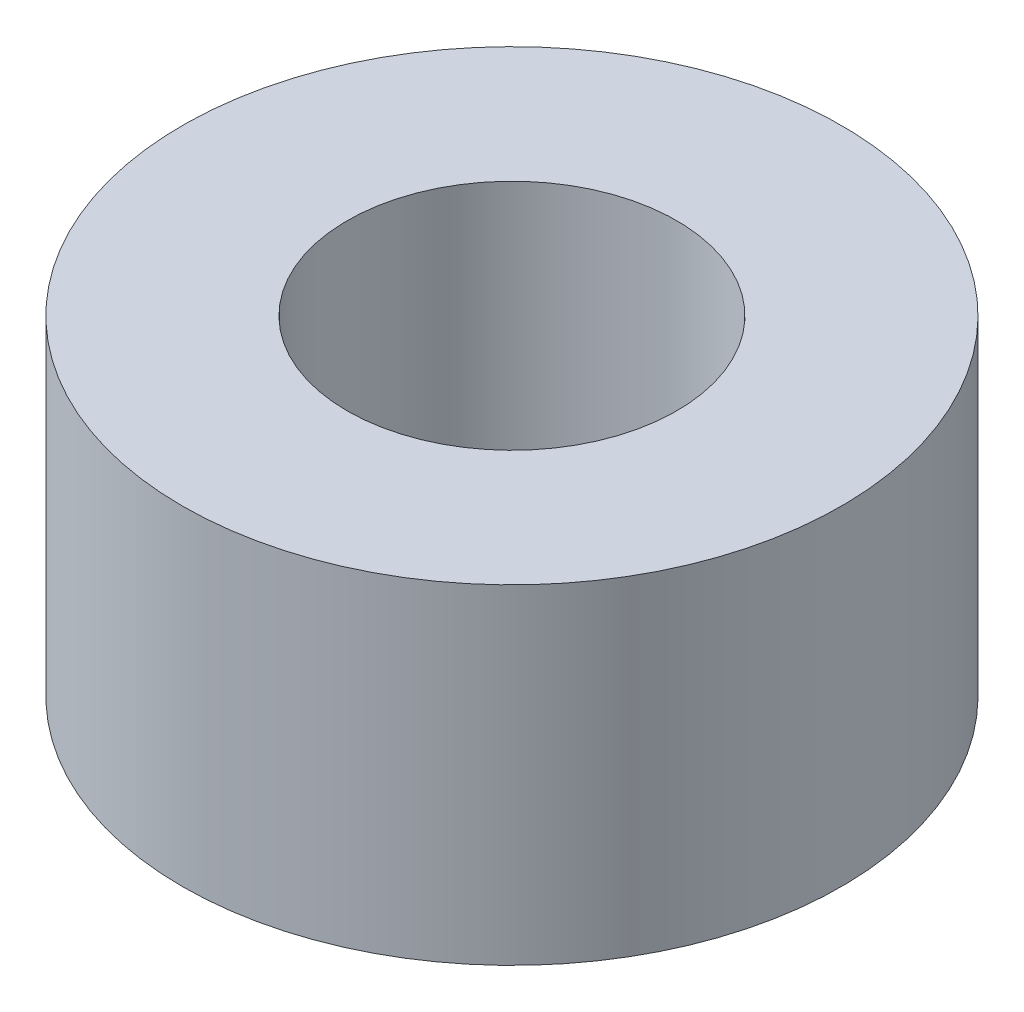
SolidWorks part; units mm, degrees
ref_plane "前视基准面" through (0, 0, 0) normal (0, 0, 1) x (1, 0, 0)
ref_plane "上视基准面" through (0, 0, 0) normal (0, 1, 0) x (1, 0, 0)
ref_plane "右视基准面" through (0, 0, 0) normal (1, 0, 0) x (0, 0, -1)
sketch "草图1" plane through (0, 0, 0) normal (0, 1, 0) x (1, 0, 0)
  circle A0 centre (0, 0) radius 3
  circle A1 centre (0, 0) radius 1.5
  dimension "D1" = 6
  dimension "D2" = 3
extrude "凸台-拉伸1" add sketch "草图1" along normal blind 3
